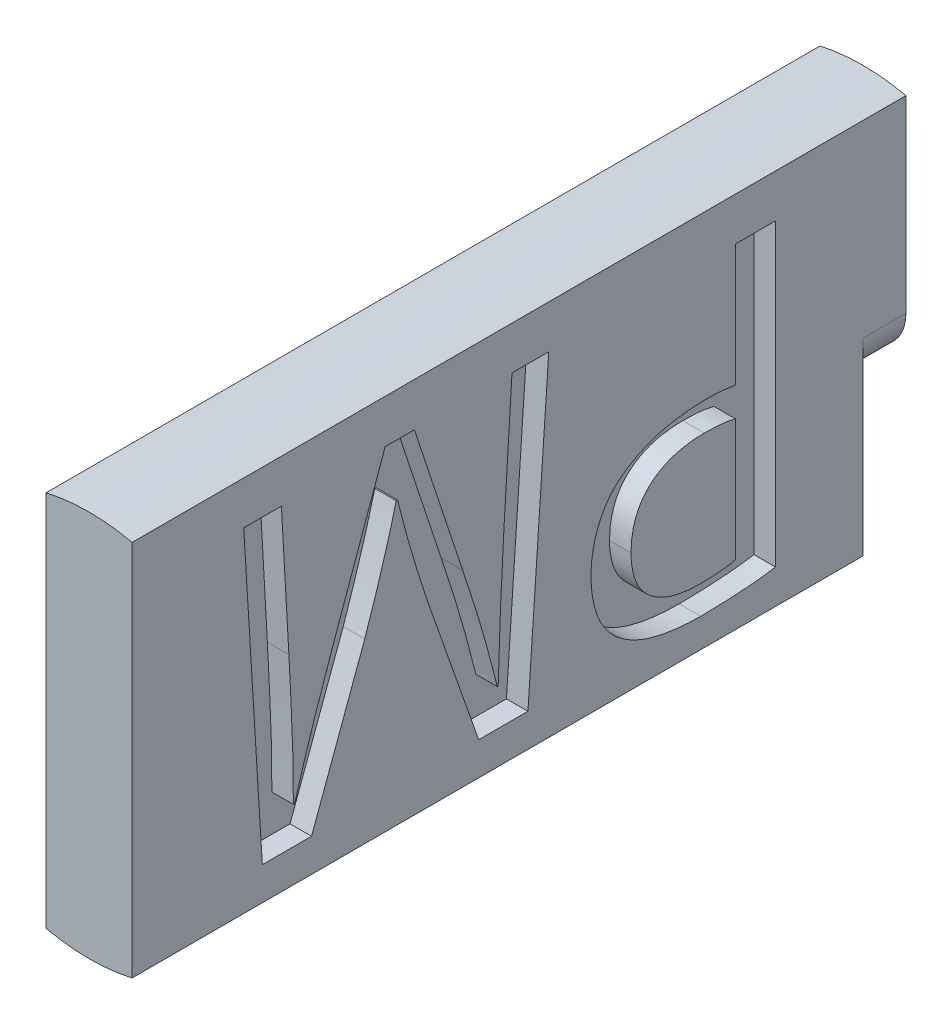
SolidWorks part; units mm, degrees
ref_plane "正面" through (0, 0, 0) normal (0, 0, 1) x (1, 0, 0)
ref_plane "平面" through (0, 0, 0) normal (0, 1, 0) x (1, 0, 0)
ref_plane "右側面" through (0, 0, 0) normal (1, 0, 0) x (0, 0, -1)
sketch "Sketch1" plane through (0, 0, 0) normal (0, 0, 1) x (1, 0, 0)
  line L0 (-1, 4.3875) -> (-1, -4.3875)
  line L1 (1, 4.3875) -> (1, -4.3875)
  arc A0 (-1, -4.3875) -> (1, -4.3875) centre (0, 0) ccw
  arc A1 (1, 4.3875) -> (-1, 4.3875) centre (0, 0) ccw
  dimension "D1" = 9
  dimension "D2" = 1
  dimension "D3" = 1
extrude "Boss-Extrude1" add sketch "Sketch1" along normal blind 17 contours A1 L0 A0 L1
sketch "Sketch3" plane through (0, 0, 0) normal (0, 0, 1) x (1, 0, 0)
  line L0 (-1, 4.3875) -> (-1, -4.3875) construction
  line L1 (1, 4.3875) -> (1, -4.3875) construction
  line L2 (-1, 4.3875) -> (-1, 0)
  line L3 (1, 0) -> (1, 4.3875)
  arc A0 (-1, 4.3875) -> (1, 4.3875) centre (0, 0) cw
  arc A1 (1, 4.3875) -> (-1, 4.3875) centre (0, 0) ccw construction
  arc A2 (-1, 0) -> (1, 0) centre (0, 0) ccw
extrude "Boss-Extrude6" add sketch "Sketch3" against normal blind 1
sketch "Sketch4" plane through (-1, 0, 0) normal (-1, 0, 0) x (0, 0, 1)
  line L0 (0, 0) -> (0, -4.3875) construction
  line L2 (17, -4.3875) -> (0, -4.3875) construction
  text T0 "AM" font "Myriad Pro" height 7
  dimension "D1" = 1.25
  dimension "D2" = 1
extrude "Cut-Extrude1" cut sketch "Sketch4" against normal blind 0.5
sketch "Sketch5" plane through (1, 0, 1) normal (1, 0, 0) x (0, 0, -1)
  line L1 (-0.25, 3.3875) -> (-12.6217, 3.3875) construction
  line L3 (1, 0) -> (1, -4.3875) construction
  line L5 (2, 4.3875) -> (-16, 4.3875) construction
  text T0 "PM" font "Myriad Pro" height 7
  dimension "D1" = 1.25
  dimension "D2" = 1
extrude "Cut-Extrude2" cut sketch "Sketch5" against normal blind 0.5
sketch "Sketch6" plane through (0, 0, 0) normal (0, 0, -1) x (-1, 0, 0)
  circle A0 centre (0, 0) radius 0.275
  dimension "D1" = 0.55
extrude "Cut-Extrude3" cut sketch "Sketch6" against normal blind 4 and the other way through all
